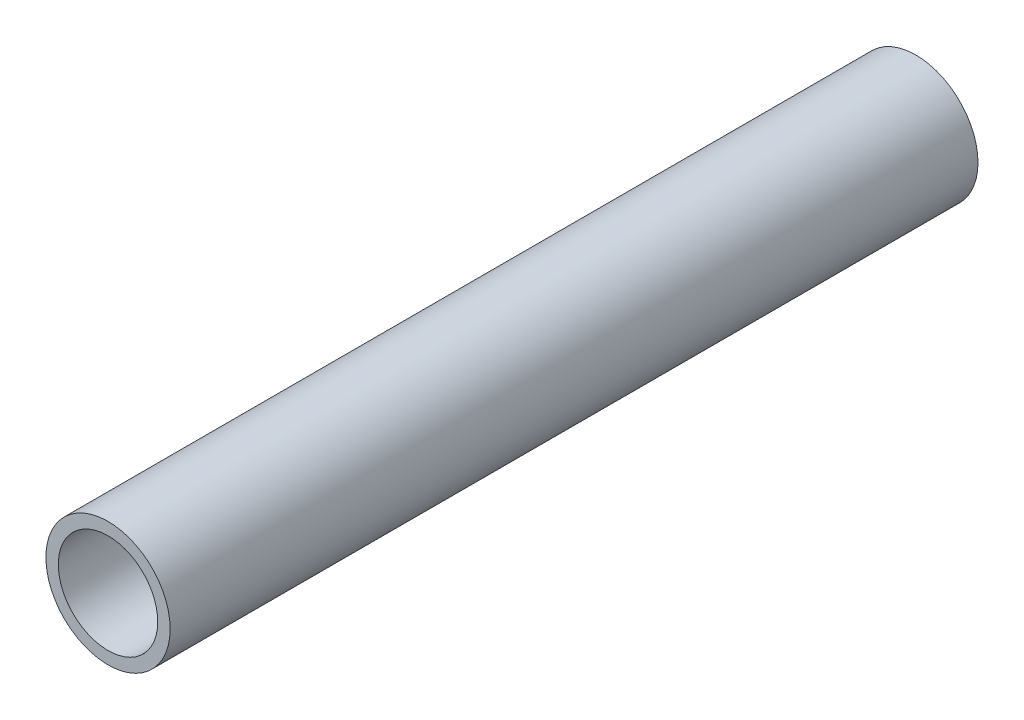
SolidWorks part; units mm, degrees
ref_plane "Front Plane" through (0, 0, 0) normal (0, 0, 1) x (1, 0, 0)
ref_plane "Top Plane" through (0, 0, 0) normal (0, 1, 0) x (1, 0, 0)
ref_plane "Right Plane" through (0, 0, 0) normal (1, 0, 0) x (0, 0, -1)
sketch "Sketch1" plane through (0, 0, 0) normal (0, 0, 1) x (1, 0, 0)
  circle A0 centre (0, 0) radius 5
  circle A1 centre (0, 0) radius 4
extrude "Boss-Extrude1" add sketch "Sketch1" along normal blind 65
